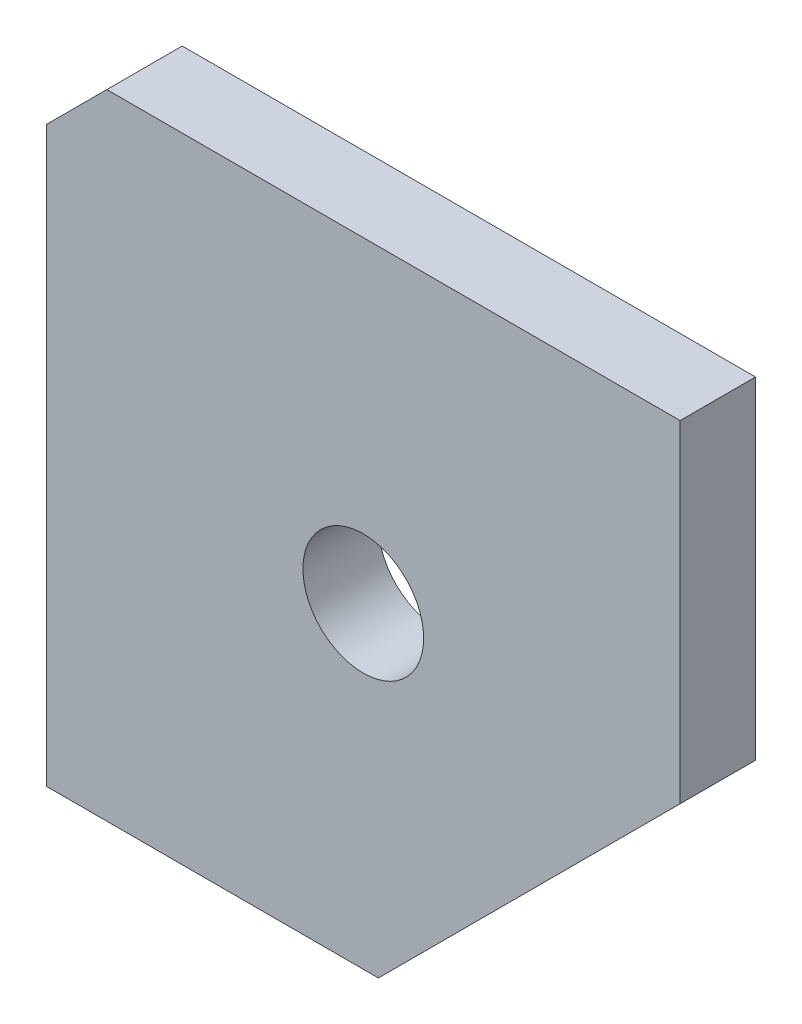
SolidWorks part; units mm, degrees
ref_plane "Front Plane" through (0, 0, 0) normal (0, 0, 1) x (1, 0, 0)
ref_plane "Top Plane" through (0, 0, 0) normal (0, 1, 0) x (1, 0, 0)
ref_plane "Right Plane" through (0, 0, 0) normal (1, 0, 0) x (0, 0, -1)
ref_plane "Plane1" through (0, 0, 0) normal (0, 0, -1) x (-1, 0, 0)
sketch "Sketch1" plane through (0, 0, 0) normal (0, 0, -1) x (-1, 0, 0)
  line L0 (-21, -1) -> (-1, -21)
  line L1 (-1, -21) -> (21, -21)
  line L2 (21, -21) -> (21, 17)
  line L3 (21, 17) -> (17, 21)
  line L4 (17, 21) -> (-21, 21)
  line L5 (-21, 21) -> (-21, -1)
  circle A0 centre (0, 0) radius 4
extrude "Boss-Extrude1" add sketch "Sketch1" against normal blind 5
